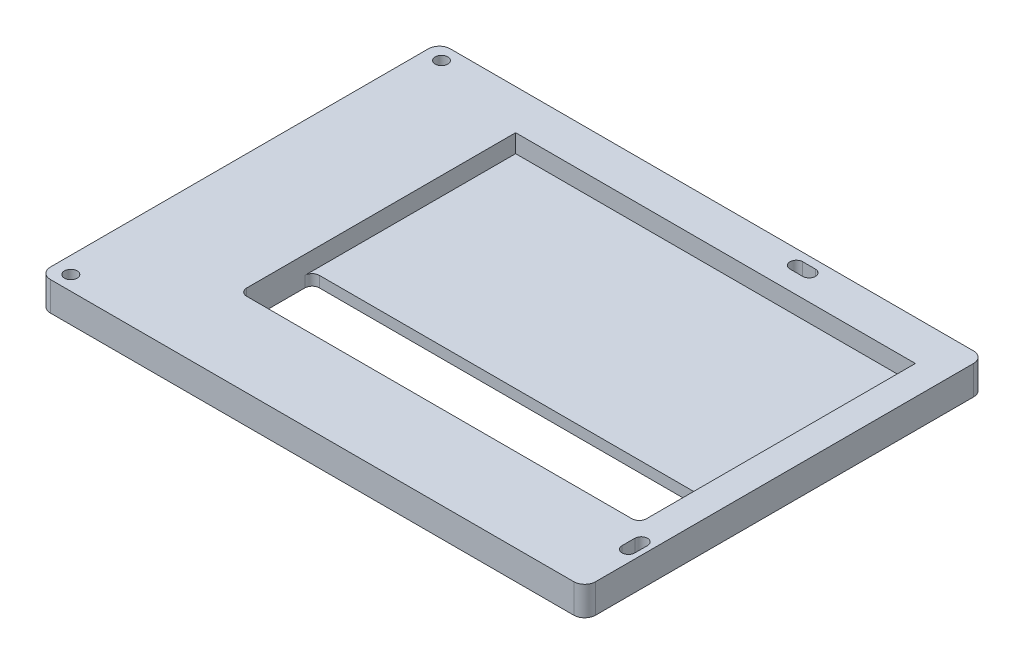
SolidWorks part; units mm, degrees
ref_plane "前视基准面" through (0, 0, 0) normal (0, 0, 1) x (1, 0, 0)
ref_plane "上视基准面" through (0, 0, 0) normal (0, 1, 0) x (1, 0, 0)
ref_plane "右视基准面" through (0, 0, 0) normal (1, 0, 0) x (0, 0, -1)
sketch "草图1" plane through (0, 0, 0) normal (0, 1, 0) x (1, 0, 0)
  line L1 (0, 0) -> (150, 0)
  line L2 (0, 0) -> (0, 110)
  line L3 (0, 110) -> (150, 110)
  line L4 (150, 0) -> (150, 110)
  dimension "D1" = 150
  dimension "D2" = 110
extrude "凸台-拉伸1" add sketch "草图1" along normal blind 8
sketch "草图2" plane through (0, 8, 0) normal (0, 1, 0) x (1, 0, 0)
  line L0 (0, 110) -> (0, 0) construction
  line L1 (150, 110) -> (0, 110) construction
  line L2 (0, 0) -> (150, 0) construction
  line L3 (150, 0) -> (150, 110) construction
  circle A0 centre (4.6, 106) radius 1.75
  circle A1 centre (4.6, 4) radius 1.75
  circle A2 centre (104, 106) radius 1.75
  circle A3 centre (146.8, 17) radius 1.75
  dimension "D1" = 3.5
  dimension "D2" = 4.6
  dimension "D3" = 4
  dimension "D4" = 3.5
  dimension "D5" = 4.6
  dimension "D6" = 4
  dimension "D7" = 3.5
  dimension "D8" = 4
  dimension "D9" = 46
  dimension "D10" = 3.5
  dimension "D11" = 3.2
  dimension "D12" = 17
extrude "切除-拉伸1" cut sketch "草图2" against normal through all
sketch "草图3" plane through (0, 8, 0) normal (0, 1, 0) x (1, 0, 0)
  line L0 (102.25, 106) -> (105.75, 106) construction
  line L1 (102.25, 107.75) -> (105.75, 107.75)
  line L2 (102.25, 104.25) -> (105.75, 104.25)
  line L3 (146.8, 15.25) -> (146.8, 18.75) construction
  line L4 (145.05, 15.25) -> (145.05, 18.75)
  line L5 (148.55, 15.25) -> (148.55, 18.75)
  circle A0 centre (104, 106) radius 1.75 construction
  arc A1 (102.25, 107.75) -> (102.25, 104.25) centre (102.25, 106) ccw
  arc A2 (105.75, 104.25) -> (105.75, 107.75) centre (105.75, 106) ccw
  circle A3 centre (146.8, 17) radius 1.75 construction
  arc A4 (145.05, 15.25) -> (148.55, 15.25) centre (146.8, 15.25) ccw
  arc A5 (148.55, 18.75) -> (145.05, 18.75) centre (146.8, 18.75) ccw
  point P5 (104, 106)
  point P11 (146.8, 17)
  dimension "D1" = 1.75
  dimension "D2" = 1.75
extrude "切除-拉伸2" cut sketch "草图3" against normal through all
sketch "草图4" plane through (0, 8, 0) normal (0, 1, 0) x (1, 0, 0)
  line L0 (150, 0) -> (150, 110) construction
  line L1 (32, 43) -> (142, 43)
  line L2 (32, 43) -> (32, 23)
  line L3 (32, 23) -> (142, 23)
  line L4 (142, 43) -> (142, 23)
  line L5 (0, 0) -> (150, 0) construction
  dimension "D1" = 20
  dimension "D2" = 110
  dimension "D3" = 8
  dimension "D4" = 23
extrude "切除-拉伸3" cut sketch "草图4" against normal through all
sketch "草图5" plane through (0, 8, 0) normal (0, 1, 0) x (1, 0, 0)
  line L1 (32, 23) -> (142, 23)
  line L2 (32, 23) -> (32, 99)
  line L3 (32, 99) -> (142, 99)
  line L4 (142, 23) -> (142, 99)
  dimension "D1" = 76
extrude "切除-拉伸4" cut sketch "草图5" against normal blind 5
fillet "圆角1" radius 2 4 edges at (32, 4, -23) (32, 1.5, -43) (142, 1.5, -43) (142, 4, -23)
fillet "圆角2" radius 3 4 edges at (0, 4, -110) (150, 4, -110) (150, 4, 0) (0, 4, 0)
